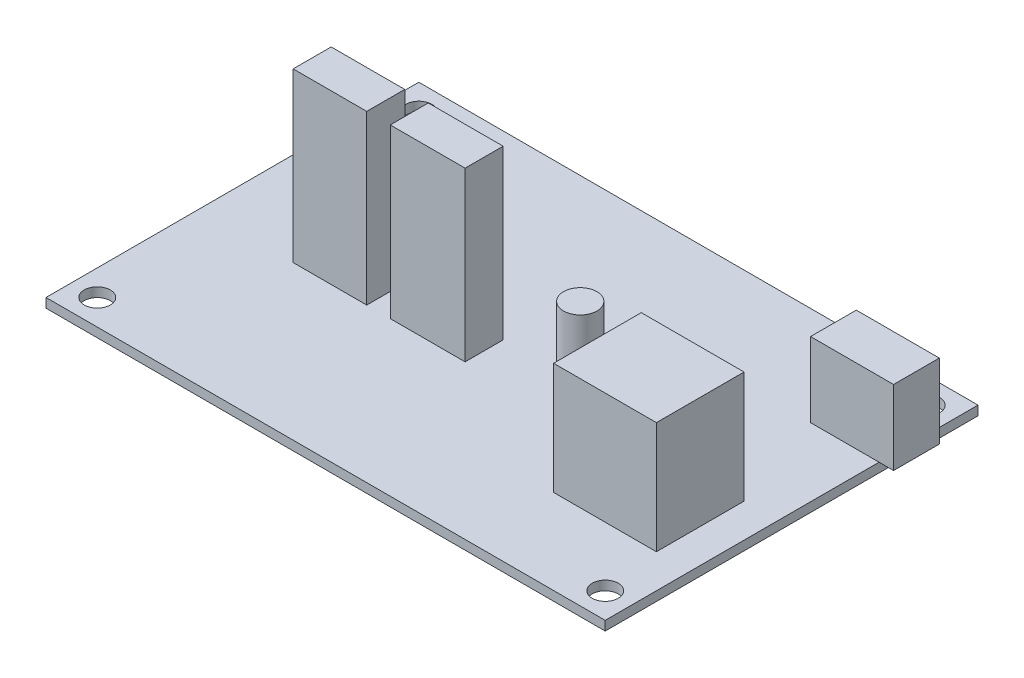
SolidWorks part; units mm, degrees
ref_plane "Front Plane" through (0, 0, 0) normal (0, 0, 1) x (1, 0, 0)
ref_plane "Top Plane" through (0, 0, 0) normal (0, 1, 0) x (1, 0, 0)
ref_plane "Right Plane" through (0, 0, 0) normal (1, 0, 0) x (0, 0, -1)
sketch "Sketch1" plane through (0, 0, 0) normal (0, 1, 0) x (1, 0, 0)
  line L1 (0, 0) -> (60, 0)
  line L2 (0, 0) -> (0, 40)
  line L3 (0, 40) -> (60, 40)
  line L4 (60, 0) -> (60, 40)
  dimension "D1" = 60
  dimension "D2" = 40
extrude "Boss-Extrude1" add sketch "Sketch1" along normal blind 1
sketch "Sketch2" plane through (0, 1, 0) normal (0, 1, 0) x (1, 0, 0)
  line L0 (2.75, 20) -> (0, 20) construction
  line L1 (2.75, 37.25) -> (57.25, 37.25) construction
  line L2 (2.75, 37.25) -> (2.75, 2.75) construction
  line L3 (2.75, 2.75) -> (57.25, 2.75) construction
  line L4 (57.25, 37.25) -> (57.25, 2.75) construction
  line L5 (0, 40) -> (0, 0) construction
  line L6 (30, 37.25) -> (30, 40) construction
  line L7 (60, 40) -> (0, 40) construction
  line L8 (30, 0) -> (30, 2.75) construction
  line L9 (0, 0) -> (60, 0) construction
  line L10 (57.25, 20) -> (60, 20) construction
  line L11 (60, 0) -> (60, 40) construction
  circle A0 centre (2.75, 37.25) radius 1.4
  circle A1 centre (57.25, 37.25) radius 1.4
  circle A2 centre (57.25, 2.75) radius 1.4
  circle A3 centre (2.75, 2.75) radius 1.4
  dimension "D3" = 2.8
  dimension "D1" = 54.5
  dimension "D2" = 34.5
extrude "Cut-Extrude1" cut sketch "Sketch2" against normal through all
sketch "Sketch3" plane through (0, 1, 0) normal (0, 1, 0) x (1, 0, 0)
  line L1 (45.3464, 9.1175) -> (56.3757, 9.1175)
  line L2 (45.3464, 9.1175) -> (45.3464, 18.5237)
  line L3 (45.3464, 18.5237) -> (56.3757, 18.5237)
  line L4 (56.3757, 9.1175) -> (56.3757, 18.5237)
  circle A0 centre (41.0167, 16.3047) radius 1.7947
  point P6 (41.0167, 16.3047)
extrude "Boss-Extrude2" add sketch "Sketch3" along normal blind 12
sketch "Sketch4" plane through (0, 1, 0) normal (0, 1, 0) x (1, 0, 0)
  line L1 (61.554, 34.2942) -> (52.6468, 34.2942)
  line L2 (61.554, 34.2942) -> (61.554, 29.3854)
  line L3 (61.554, 29.3854) -> (52.6468, 29.3854)
  line L4 (52.6468, 34.2942) -> (52.6468, 29.3854)
extrude "Boss-Extrude3" add sketch "Sketch4" along normal blind 8
sketch "Sketch5" plane through (0, 1, 0) normal (0, 1, 0) x (1, 0, 0)
  line L1 (10.0168, 20.5801) -> (17.913, 20.5801)
  line L2 (10.0168, 20.5801) -> (10.0168, 16.5015)
  line L3 (10.0168, 16.5015) -> (17.913, 16.5015)
  line L4 (17.913, 20.5801) -> (17.913, 16.5015)
  line L5 (20.4358, 20.5801) -> (28.4665, 20.5801)
  line L6 (20.4358, 20.5801) -> (20.4358, 16.5015)
  line L7 (20.4358, 16.5015) -> (28.4665, 16.5015)
  line L8 (28.4665, 20.5801) -> (28.4665, 16.5015)
extrude "Boss-Extrude4" add sketch "Sketch5" along normal blind 18
